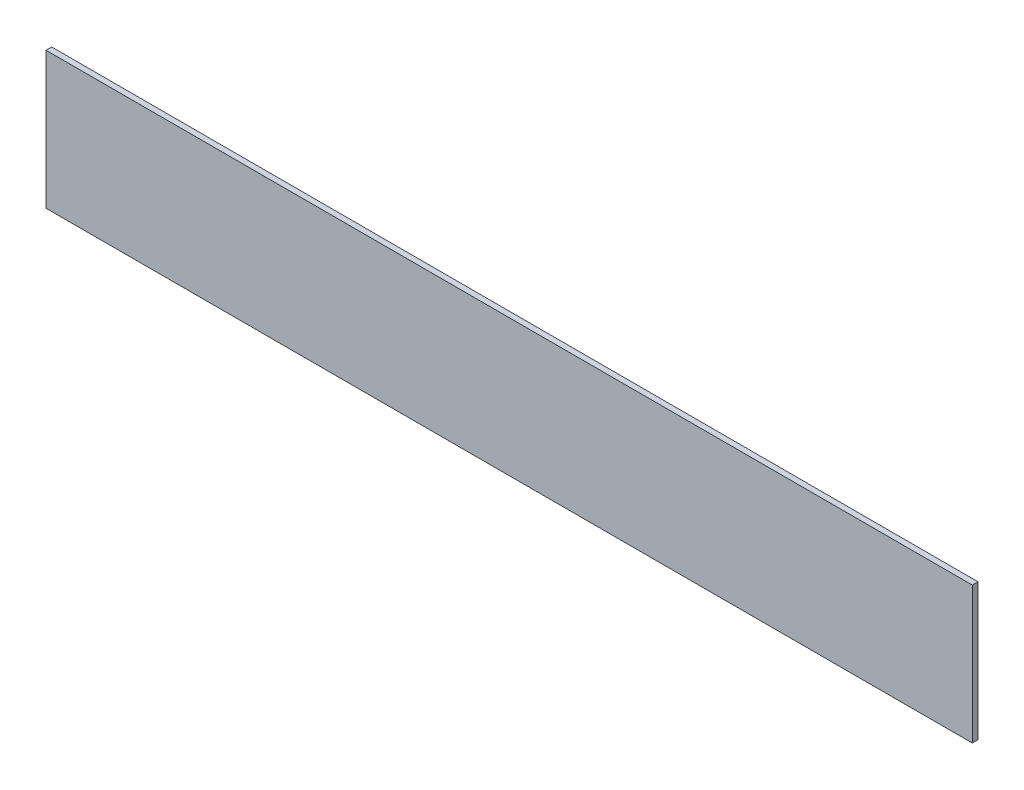
SolidWorks part; units mm, degrees
material "Pine"
ref_plane "Front Plane" through (0, 0, 0) normal (0, 0, 1) x (1, 0, 0)
ref_plane "Top Plane" through (0, 0, 0) normal (0, 1, 0) x (1, 0, 0)
ref_plane "Right Plane" through (0, 0, 0) normal (1, 0, 0) x (0, 0, -1)
sketch "Sketch1" plane through (0, 0, 0) normal (0, 0, 1) x (1, 0, 0)
  line L1 (-515.874, 76.2) -> (515.874, 76.2)
  line L2 (-515.874, 76.2) -> (-515.874, -76.2)
  line L3 (-515.874, -76.2) -> (515.874, -76.2)
  line L4 (515.874, 76.2) -> (515.874, -76.2)
  line L5 (-515.874, 76.2) -> (515.874, -76.2) construction
  line L6 (-515.874, -76.2) -> (515.874, 76.2) construction
  point P0 (0, 0)
  dimension "D1" = 152.4
  dimension "D2" = 1031.748
extrude "Boss-Extrude1" add sketch "Sketch1" along normal blind 6.35
